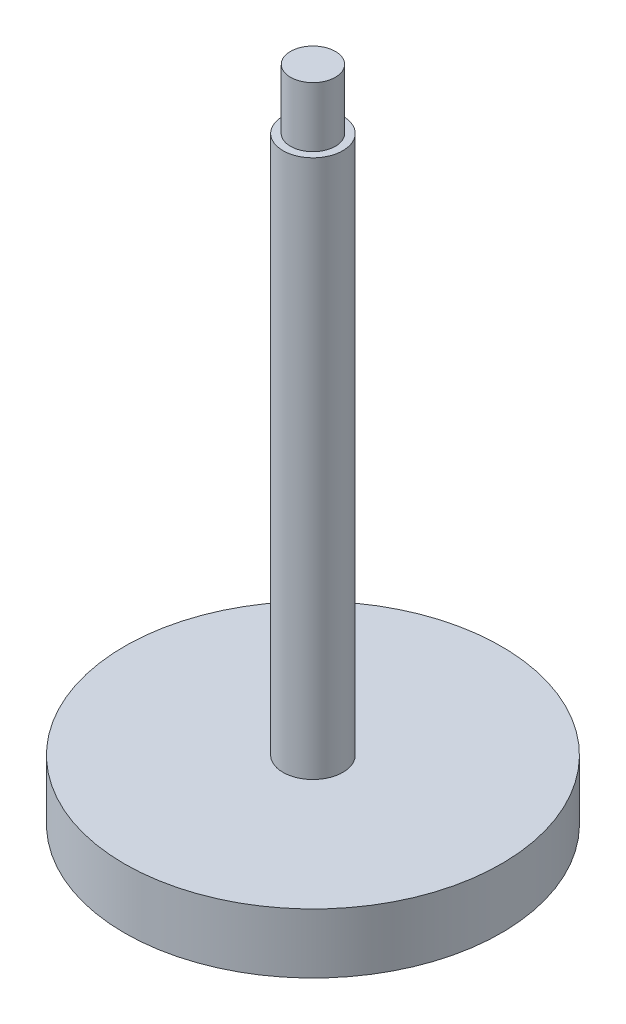
SolidWorks part; units mm, degrees
ref_plane "Front Plane" through (0, 0, 0) normal (0, 0, 1) x (1, 0, 0)
ref_plane "Top Plane" through (0, 0, 0) normal (0, 1, 0) x (1, 0, 0)
ref_plane "Right Plane" through (0, 0, 0) normal (1, 0, 0) x (0, 0, -1)
sketch "Sketch1" plane through (0, 0, 0) normal (0, 1, 0) x (1, 0, 0)
  circle A0 centre (0, 0) radius 63
  dimension "D1" = 126
extrude "Boss-Extrude1" add sketch "Sketch1" along normal blind 20
sketch "Sketch2" plane through (0, 20, 0) normal (0, 1, 0) x (1, 0, 0)
  circle A0 centre (0, 0) radius 10
  dimension "D1" = 20
extrude "Boss-Extrude2" add sketch "Sketch2" along normal blind 200
sketch "Sketch3" plane through (0, 220, 0) normal (0, 1, 0) x (1, 0, 0)
  circle A0 centre (0, 0) radius 7.5
  dimension "D1" = 15
extrude "Cut-Extrude1" cut sketch "Sketch3" against normal blind 20 flip side to cut
